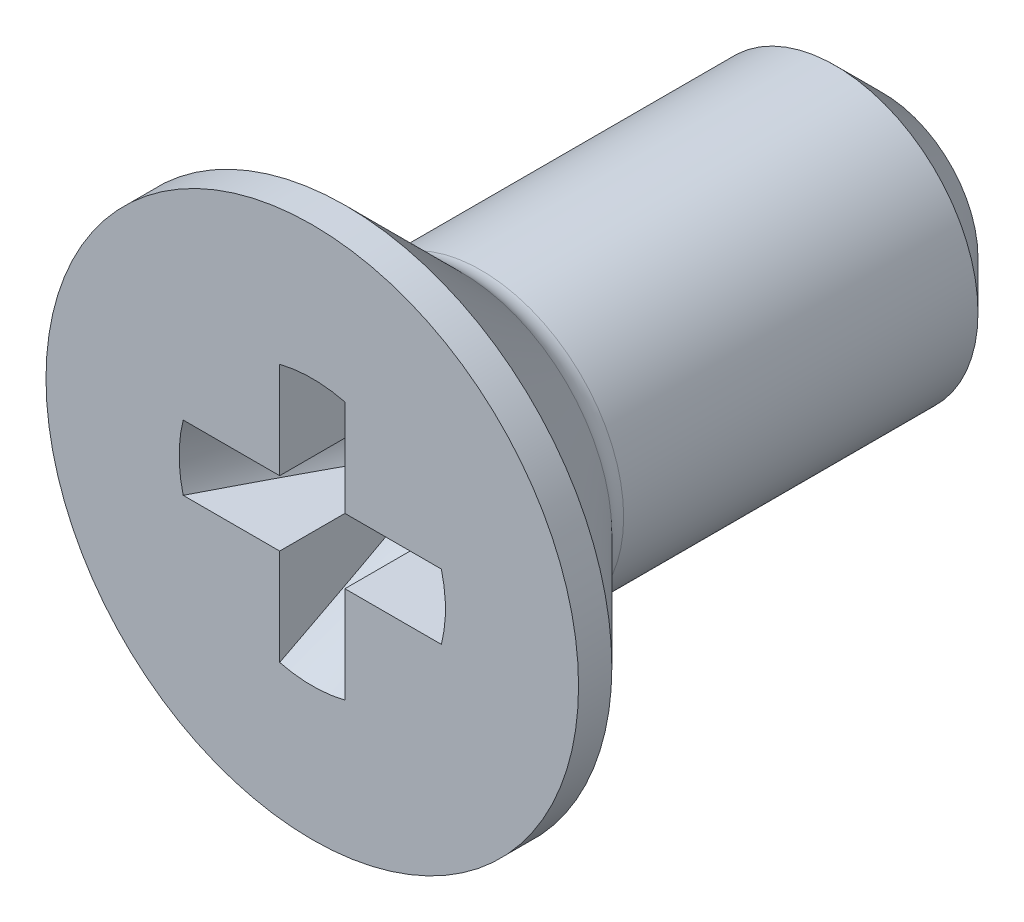
SolidWorks part; units mm, degrees
material "1060 Alloy"
ref_plane "Спереди" through (0, 0, 0) normal (0, 0, 1) x (1, 0, 0)
ref_plane "Сверху" through (0, 0, 0) normal (0, 1, 0) x (1, 0, 0)
ref_plane "Справа" through (0, 0, 0) normal (1, 0, 0) x (0, 0, -1)
sketch "Sketch1" plane through (0, 0, 0) normal (1, 0, 0) x (0, 0, -1)
  line L0 (0, 0) -> (6, 0) construction
  line L1 (0, 0) -> (0, 2.8)
  line L2 (0, 2.8) -> (0.35, 2.8)
  line L3 (0.35, 2.8) -> (1.65, 1.5)
  line L4 (1.65, 1.5) -> (6, 1.5)
  line L5 (6, 1.5) -> (6, 0)
  line L6 (0.35, -2.8) -> (1.65, -1.5) construction
  line L7 (0, 0) -> (6, 0)
  dimension "D" = 5.6
  dimension "D1" = 90
  dimension "k" = 1.65
  dimension "d2" = 3
  dimension "L" = 6
revolve "RevolveBase" add sketch "Sketch1" angle 360 about L7
cosmetic thread "Cosmetic Thread1" parameters "D1"=4.35, "D2"=2.459
chamfer "ChamferRod" distance 0.5 angle 45 1 edges at (1.5, 0, -6)
sketch "Sketch4" plane through (0, 0, 0) normal (0, 0, 1) x (1, 0, 0)
  line L1 (-0.4, -2.8) -> (0.4, -2.8)
  line L2 (-0.4, -2.8) -> (-0.4, 2.8)
  line L3 (-0.4, 2.8) -> (0.4, 2.8)
  line L4 (0.4, -2.8) -> (0.4, 2.8)
  line L5 (-0.4, -2.8) -> (0.4, 2.8) construction
  line L6 (-0.4, 2.8) -> (0.4, -2.8) construction
  point P0 (0, 0)
  dimension "D1" = 5.6
  dimension "bh" = 0.8
extrude "Slot" [suppressed] cut sketch "Sketch4" against normal blind 0.6
sketch "Sketch3" plane through (0, 0, 0) normal (0, 0, 1) x (1, 0, 0)
  line L0 (0, 2.8) -> (0, 0) construction
  line L1 (0, 0) -> (2.8, 0) construction
  line L2 (-0.3429, 0) -> (0.3429, 0)
  line L3 (0.3429, 0) -> (0.3429, 1.3573)
  line L4 (-0.3429, 0) -> (-0.3429, 1.3573)
  line L5 (0.3429, 0) -> (-0.3429, 0.6859) construction
  arc A0 (0.3429, 1.3573) -> (-0.3429, 1.3573) centre (0, 0) ccw
  circle A1 centre (0, 0) radius 2.8 construction
  point P1 (0, 1.4)
  dimension "m" = 2.8
  dimension "D1" = 45
  dimension "b" = 0.97
extrude "Cross" cut sketch "Sketch3" against normal blind 2.8
pattern_circular "CirPattern1" count 4 over 360 about axis through (0, 0, 0) along (0, 0, 1) of "Cross"
sketch "Sketch5" plane through (0, 0, 0) normal (1, 0, 0) x (0, 0, -1)
  line L2 (2.8, 0) -> (2.8, 1.9)
  line L6 (0, 2.8) -> (0, -2.8) construction
  line L7 (0, 1.9) -> (0, 1.4)
  line L8 (0, 1.4) -> (1.5344, 0.635)
  line L9 (1.5344, 0.635) -> (1.872, 0)
  line L10 (1.872, 0) -> (2.8, 0)
  line L11 (0, 0) -> (6, 0) construction
  line L12 (6, -1) -> (6, 1) construction
  line L15 (2.8, 1.9) -> (0, 1.9)
  dimension "D1" = 2.8
  dimension "g" = 1.27
  dimension "D2" = 2.8
  dimension "D3" = 0.5
  dimension "D5" = 28
  dimension "D7" = 26.5
revolve "RevolveRod" add sketch "Sketch5" angle 360 about L11
sketch "Sketch7" plane through (0, 0, 0) normal (1, 0, 0) x (0, 0, -1)
  line L0 (0, 0) -> (2.5345, 0) construction
  line L2 (-21.85, 25) -> (1.65, 1.5)
  line L3 (1.65, 1.5) -> (2.8, 1.5)
  line L5 (2.8, 1.5) -> (2.8, 25)
  line L6 (2.8, 25) -> (-21.85, 25)
  line L7 (0, 2.8) -> (0, -2.8) construction
  dimension "D1" = 3
  dimension "D2" = 1.65
  dimension "D3" = 2.8
  dimension "D4" = 135
  dimension "D5" = 50
revolve "CutRod" cut sketch "Sketch7" angle 360 about L0
sketch "Sketch8" plane through (0, 0, 0) normal (1, 0, 0) x (0, 0, -1)
  line L0 (0, 0) -> (1.65, 0) construction
  line L1 (1.65, 0) -> (1.65, 1.5) construction
  line L2 (1.65, 1.5) -> (0.9, 2.25)
  dimension "D1" = 45
  dimension "D2" = 1.65
  dimension "D3" = 3
  dimension "D4" = 4.5
surface "Surface" sketch "Sketch8" parameters "D1"=360
fillet "Fillet1" radius 0.3 1 edges at (0, -1.5, -1.65)
equation "\"D1@Sketch4\"=\"D@Sketch1\""
equation "\"D1@Cross\" = \"m@Sketch3\""
equation "\"D1@Sketch5\"=\"m@Sketch3\""
equation "\"D2@Sketch5\"=\"m@Sketch3\""
equation "\"D1@Sketch7\"=\"d2@Sketch1\""
equation "\"D2@Sketch7\"=\"k@Sketch1\""
equation "\"D3@Sketch7\"=\"m@Sketch3\""
equation "\"D2@Sketch8\" = \"k@Sketch1\""
equation "\"D3@Sketch8\" = \"d2@Sketch1\""
equation "\"D4@Sketch8\" = 1.5 * \"d2@Sketch1\""
equation "\"D1@Fillet1\"=\"d2@Sketch1\"*0.1"
